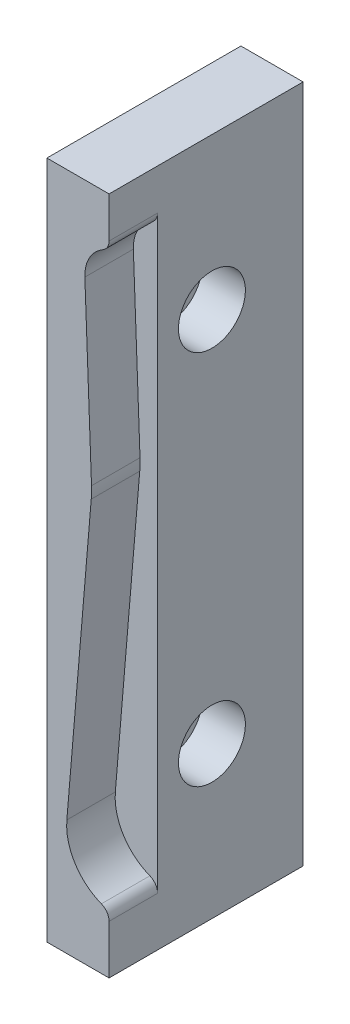
SolidWorks part; units mm, degrees
material "6061-T6 (SS)"
ref_plane "X-Y Datum" through (0, 0, 0) normal (0, 0, 1) x (1, 0, 0)
ref_plane "X-Z Datum" through (0, 0, 0) normal (0, 1, 0) x (1, 0, 0)
ref_plane "Y-Z Datum" through (0, 0, 0) normal (1, 0, 0) x (0, 0, -1)
sketch "Sketch1" plane through (0, 0, 0) normal (0, 0, 1) x (1, 0, 0)
  line L1 (-3.175, 148.6803) -> (-19.4564, 148.6803)
  line L2 (-9.5183, 126.6428) -> (-7.7759, 80.2121)
  line L3 (-7.8475, 77.1297) -> (-14.2372, 1.1981)
  line L6 (-19.4564, 148.6803) -> (-19.4564, -29.1197)
  line L7 (-19.4564, -29.1197) -> (-3.175, -29.1197)
  line L9 (-3.175, 148.6803) -> (-3.175, 135.9803)
  line L10 (-3.175, -13.9303) -> (-3.175, -29.1197)
  arc A0 (-14.2372, 1.1981) -> (-3.175, -13.9303) centre (0, 0) ccw
  arc A1 (-9.5183, 126.6428) -> (-3.175, 135.9803) centre (0, 127) cw
  arc A2 (-7.8475, 77.1297) -> (-7.7759, 80.2121) centre (-33.1581, 79.2596) ccw
  dimension "D1" = 9.525
  dimension "D2" = 25.4
  dimension "D3" = 3.175
  dimension "D4" = 177.8
  dimension "D9" = 14.2875
  dimension "D5" = 12.7
  dimension "D6" = 16.2814
  dimension "D7" = 46.4307
  dimension "D12" = 7.7759
  dimension "D13" = 7.8475
extrude "Boss-Extrude1" add sketch "Sketch1" along normal mid plane 12.7
fillet "Fillet1" radius 3.175 2 edges at (-3.175, 135.9803, 0) (-3.175, -13.9303, 0)
sketch "Sketch3" plane through (0, 0, -6.35) normal (0, 0, -1) x (-1, 0, 0)
  line L1 (3.175, 148.6803) -> (19.4564, 148.6803)
  line L2 (3.175, 148.6803) -> (3.175, -29.1197)
  line L3 (3.175, -29.1197) -> (19.4564, -29.1197)
  line L4 (19.4564, 148.6803) -> (19.4564, -29.1197)
extrude "Boss-Extrude2" add sketch "Sketch3" along normal blind 38.1
sketch "Sketch4" plane through (-3.175, 0, 0) normal (1, 0, 0) x (0, 0, -1)
  line L0 (44.45, 148.6803) -> (44.45, -29.1197) construction
  line L1 (20.574, 108.992) -> (20.574, 10.5685) construction
  circle A2 centre (20.574, 108.992) radius 6.7437
  circle A3 centre (20.574, 10.5685) radius 6.7437
  point P4 (44.45, 59.7803)
  point P7 (20.574, 59.7803)
  point P9 (20.574, 108.992)
  point P10 (20.574, 10.5685)
  dimension "D3" = 13.4874
  dimension "D1" = 98.4235
  dimension "D2" = 23.876
extrude "Cut-Extrude1" cut sketch "Sketch4" against normal through all
sketch "Sketch5" plane through (-3.175, 0, 0) normal (1, 0, 0) x (0, 0, -1)
  circle A0 centre (20.574, 108.992) radius 8.7641
  circle A1 centre (20.574, 10.5685) radius 8.7641
  dimension "D1" = 17.5282
extrude "Cut-Extrude2" cut sketch "Sketch5" against normal offset from surface (11.3284 mm away) 4.953 up to face at (-19.4564, 115.7357, -20.574)
sketch "Sketch6" plane through (-3.175, 0, 0) normal (1, 0, 0) x (0, 0, -1)
  circle A0 centre (23.7998, -13.6257) radius 5.7547
  circle A1 centre (23.7998, 65.7493) radius 5.7547
